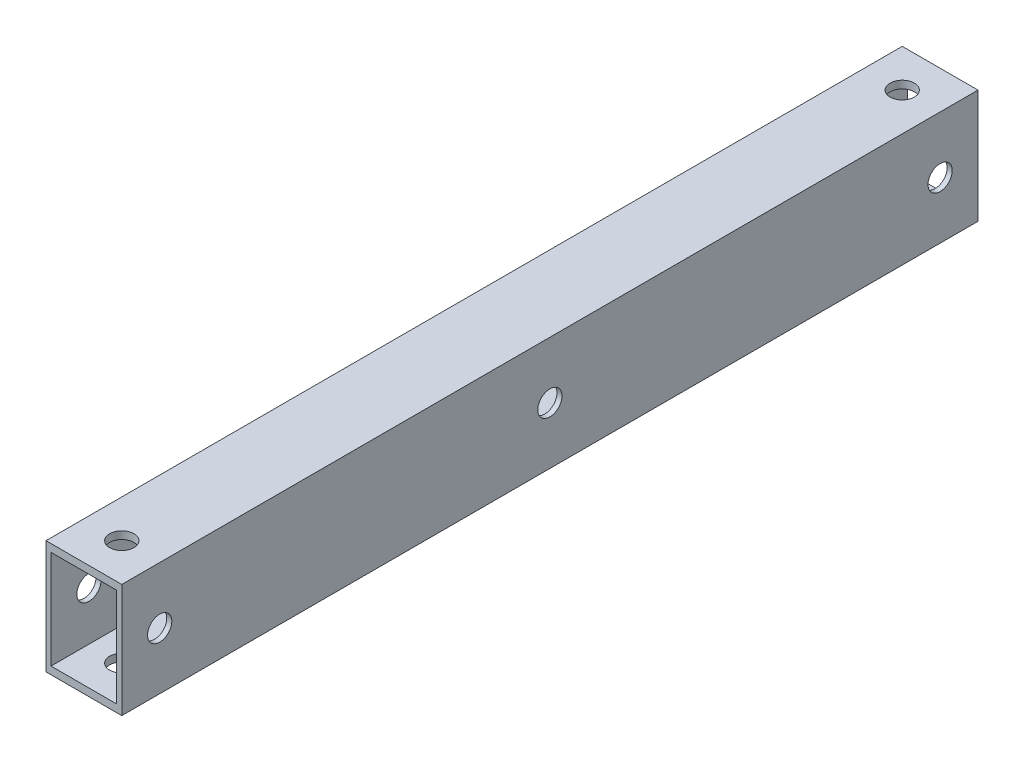
SolidWorks part; units mm, degrees
ref_plane "正面" through (0, 0, 0) normal (0, 0, 1) x (1, 0, 0)
ref_plane "平面" through (0, 0, 0) normal (0, 1, 0) x (1, 0, 0)
ref_plane "右側面" through (0, 0, 0) normal (1, 0, 0) x (0, 0, -1)
sketch "ｽｹｯﾁ1" plane through (0, 0, 0) normal (0, 0, 1) x (1, 0, 0)
  line L1 (-5, -7.5) -> (5, -7.5)
  line L2 (-5, -7.5) -> (-5, 7.5)
  line L3 (-5, 7.5) -> (5, 7.5)
  line L4 (5, -7.5) -> (5, 7.5)
  line L5 (-5, -7.5) -> (5, 7.5) construction
  line L6 (-5, 7.5) -> (5, -7.5) construction
  line L7 (-4.3333, -6.5) -> (4.3333, -6.5)
  line L8 (-4.3333, -6.5) -> (-4.3333, 6.5)
  line L9 (-4.3333, 6.5) -> (4.3333, 6.5)
  line L10 (4.3333, -6.5) -> (4.3333, 6.5)
  line L11 (-4.3333, -6.5) -> (4.3333, 6.5) construction
  line L12 (-4.3333, 6.5) -> (4.3333, -6.5) construction
  point P0 (0, 0)
  point P6 (0, 0)
  dimension "D1" = 1
  dimension "D2" = 10
  dimension "D3" = 15
extrude "ﾎﾞｽ - 押し出し1" add sketch "ｽｹｯﾁ1" along normal blind 56.5
sketch "ｽｹｯﾁ2" plane through (5, 0, 0) normal (1, 0, 0) x (0, 0, -1)
  line L0 (-56.5, -7.5) -> (0, -7.5) construction
  line L1 (0, -7.5) -> (0, 7.5) construction
  circle A0 centre (0, 0) radius 1.6
  dimension "D1" = 3.2
  dimension "D2" = 7.5
  dimension "D3" = 0
extrude "ｶｯﾄ - 押し出し1" cut sketch "ｽｹｯﾁ2" against normal through all
sketch "ｽｹｯﾁ3" plane through (0, 7.5, 0) normal (0, 1, 0) x (1, 0, 0)
  line L0 (5, -56.5) -> (-5, -56.5) construction
  line L1 (-5, -56.5) -> (-5, 0) construction
  circle A0 centre (0, -51.5) radius 1.6
  dimension "D1" = 3.2
  dimension "D2" = 5
  dimension "D3" = 5
extrude "ｶｯﾄ - 押し出し2" cut sketch "ｽｹｯﾁ3" against normal through all
sketch "ｽｹｯﾁ4" plane through (-5, 0, 0) normal (-1, 0, 0) x (0, 0, 1)
  line L0 (56.5, 7.5) -> (56.5, -7.5) construction
  line L1 (56.5, 7.5) -> (0, 7.5) construction
  circle A0 centre (51.5, 0) radius 1.6
  dimension "D1" = 3.2
  dimension "D2" = 5
  dimension "D3" = 7.5
extrude "ｶｯﾄ - 押し出し3" cut sketch "ｽｹｯﾁ4" against normal through all
mirror "ﾐﾗｰ1" about plane through (0, 0, 0) normal (0, 0, -1) of "ｶｯﾄ - 押し出し3", "ｶｯﾄ - 押し出し1", "ﾎﾞｽ - 押し出し1", "ｶｯﾄ - 押し出し2"
